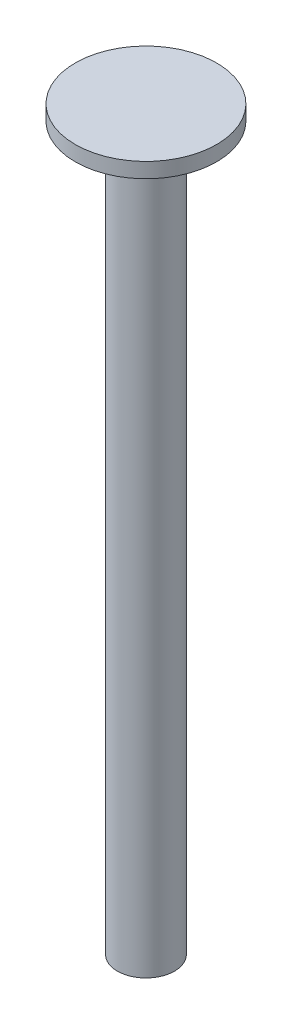
SolidWorks part; units mm, degrees
ref_plane "Front Plane" through (0, 0, 0) normal (0, 0, 1) x (1, 0, 0)
ref_plane "Top Plane" through (0, 0, 0) normal (0, 1, 0) x (1, 0, 0)
ref_plane "Right Plane" through (0, 0, 0) normal (1, 0, 0) x (0, 0, -1)
sketch "Эскиз1" plane through (0, 0, 0) normal (0, 1, 0) x (1, 0, 0)
  circle A0 centre (0, 0) radius 0.95
extrude "Бобышка-Вытянуть1" add sketch "Эскиз1" along normal blind 24
sketch "Эскиз3" plane through (0, 24, 0) normal (0, 1, 0) x (1, 0, 0)
  circle A0 centre (0, 0) radius 2.35
extrude "Бобышка-Вытянуть2" add sketch "Эскиз3" along normal blind 0.5
